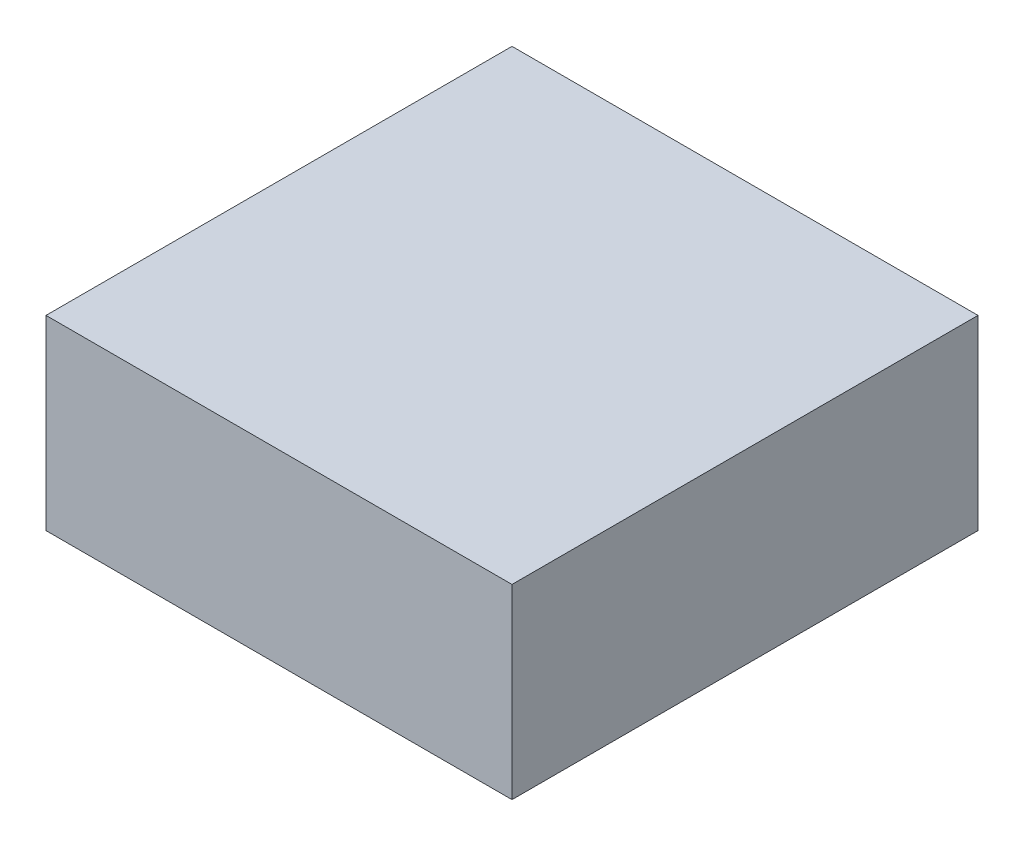
SolidWorks part; units mm, degrees
ref_plane "Ön Düzlem" through (0, 0, 0) normal (0, 0, 1) x (1, 0, 0)
ref_plane "Üst Düzlem" through (0, 0, 0) normal (0, 1, 0) x (1, 0, 0)
ref_plane "Sağ Düzlem" through (0, 0, 0) normal (1, 0, 0) x (0, 0, -1)
sketch "Çizim1" plane through (0, 0, 0) normal (0, 1, 0) x (1, 0, 0)
  line L1 (-10, -10) -> (10, -10)
  line L2 (-10, -10) -> (-10, 10)
  line L3 (-10, 10) -> (10, 10)
  line L4 (10, -10) -> (10, 10)
  line L5 (-10, -10) -> (10, 10) construction
  line L6 (-10, 10) -> (10, -10) construction
  point P0 (0, 0)
  dimension "D1" = 20
  dimension "D2" = 20
extrude "Yükseklik-Ekstrüzyon1" add sketch "Çizim1" along normal blind 8
